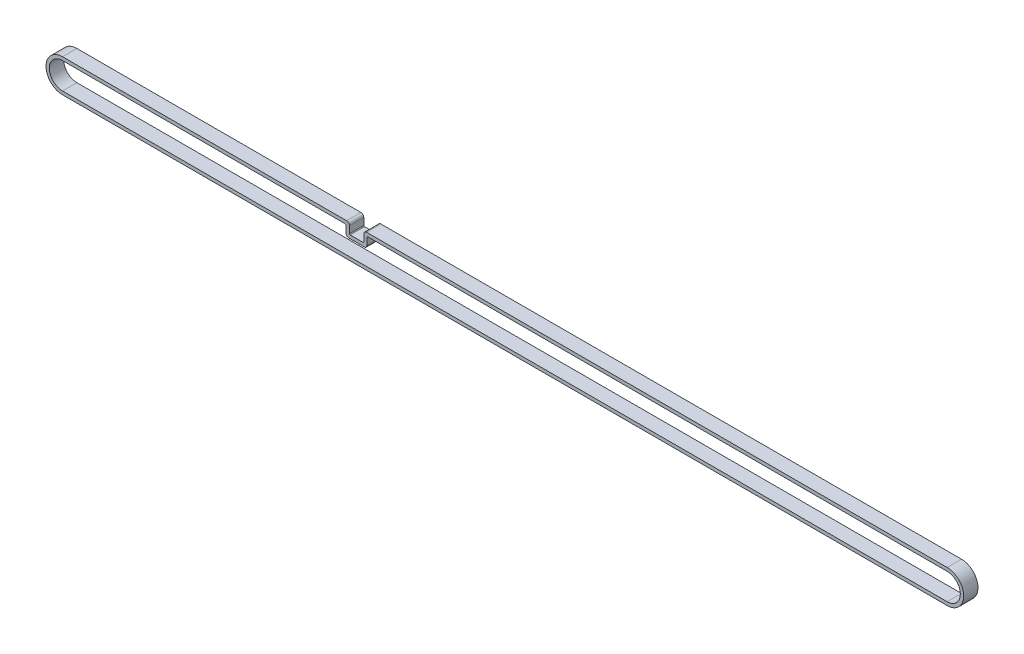
SolidWorks part; units mm, degrees
material "aluminio"
ref_plane "Alzado" through (0, 0, 0) normal (0, 0, 1) x (1, 0, 0)
ref_plane "Planta" through (0, 0, 0) normal (0, 1, 0) x (1, 0, 0)
ref_plane "Vista lateral" through (0, 0, 0) normal (1, 0, 0) x (0, 0, -1)
sketch "Croquis1" plane through (0, 0, 0) normal (0, 0, 1) x (1, 0, 0)
  line L0 (0, 0) -> (370, 0) construction
  line L1 (0, 5.5) -> (118.6, 5.5)
  line L2 (0, -5.5) -> (370, -5.5)
  line L3 (0, 6.9) -> (120, 6.9)
  line L4 (0, -6.9) -> (370, -6.9)
  line L5 (120, 6.9) -> (120, 2.5)
  line L6 (120, 2.5) -> (126, 2.5)
  line L7 (126, 2.5) -> (126, 6.9)
  line L8 (118.6, 5.5) -> (118.6, 1.1)
  line L9 (118.6, 1.1) -> (127.4, 1.1)
  line L10 (127.4, 1.1) -> (127.4, 5.5)
  line L11 (120, 5.5) -> (120, 2.5) construction
  line L12 (127.4, 5.5) -> (370, 5.5)
  line L13 (0, 5.5) -> (370, 5.5) construction
  line L14 (126, 2.5) -> (126, 5.5) construction
  line L15 (126, 6.9) -> (370, 6.9)
  line L17 (0, 6.9) -> (370, 6.9) construction
  arc A0 (0, 5.5) -> (0, -5.5) centre (0, 0) ccw
  arc A1 (370, -5.5) -> (370, 5.5) centre (370, 0) ccw
  arc A2 (370, -6.9) -> (370, 6.9) centre (370, 0) ccw
  arc A3 (0, 6.9) -> (0, -6.9) centre (0, 0) ccw
  point P3 (185, 0)
  dimension "D2" = 5.5
  dimension "D1" = 370
  dimension "D4" = 1.4
  dimension "D5" = 6
  dimension "D6" = 3
  dimension "D7" = 120
  dimension "D3" = 1.4
extrude "Saliente-Extruir1" add sketch "Croquis1" along normal blind 6
fillet "Redondeo1" radius 0.3 4 edges at (127.4, 5.5, 3) (118.6, 5.5, 3) (126, 2.5, 3) (120, 2.5, 3)
fillet "Redondeo2" radius 1.2 4 edges at (118.6, 1.1, 3) (127.4, 1.1, 3) (126, 6.9, 3) (120, 6.9, 3)
